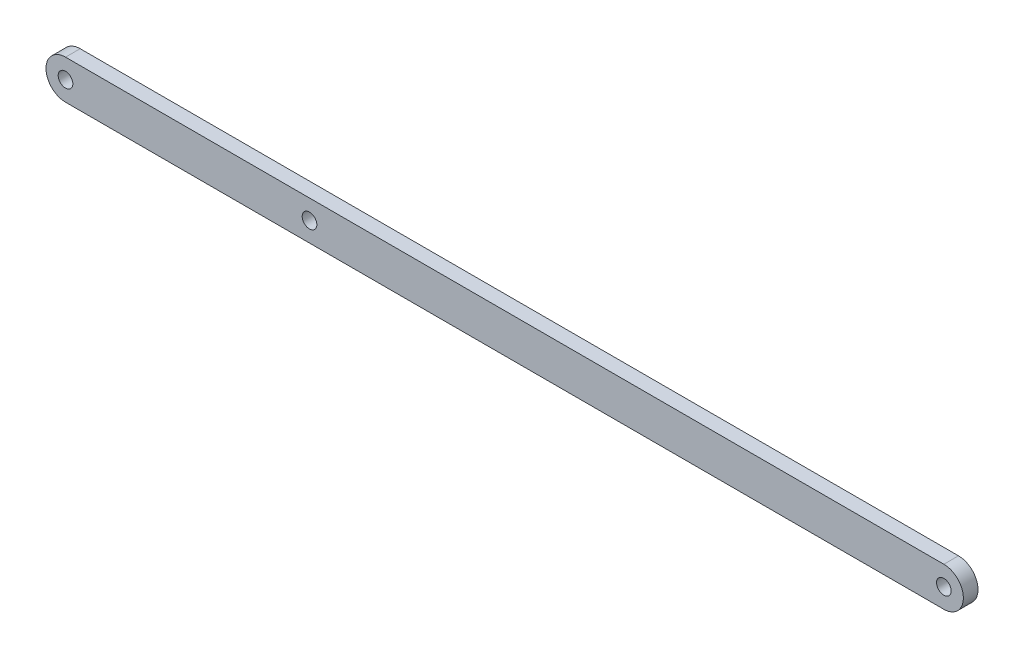
SolidWorks part; units mm, degrees
ref_plane "Front Plane" through (0, 0, 0) normal (0, 0, 1) x (1, 0, 0)
ref_plane "Top Plane" through (0, 0, 0) normal (0, 1, 0) x (1, 0, 0)
ref_plane "Right Plane" through (0, 0, 0) normal (1, 0, 0) x (0, 0, -1)
sketch "Sketch1" plane through (0, 0, 0) normal (0, 0, 1) x (1, 0, 0)
  line L0 (-180, 0) -> (180, 0) construction
  line L1 (-180, 8) -> (180, 8)
  line L2 (-180, -8) -> (180, -8)
  arc A0 (-180, 8) -> (-180, -8) centre (-180, 0) ccw
  arc A1 (180, -8) -> (180, 8) centre (180, 0) ccw
  circle A2 centre (-180, 0) radius 3
  circle A3 centre (-80, 0) radius 3
  circle A4 centre (180, 0) radius 3
  point P2 (0, 0)
  dimension "D3" = 8
  dimension "D4" = 6
  dimension "D5" = 6
  dimension "D6" = 6
  dimension "D1" = 360
  dimension "D2" = 100
extrude "Boss-Extrude1" add sketch "Sketch1" against normal blind 6
scale "Scale1" scale about centroid uniform scaling yes scale factor 0.5
